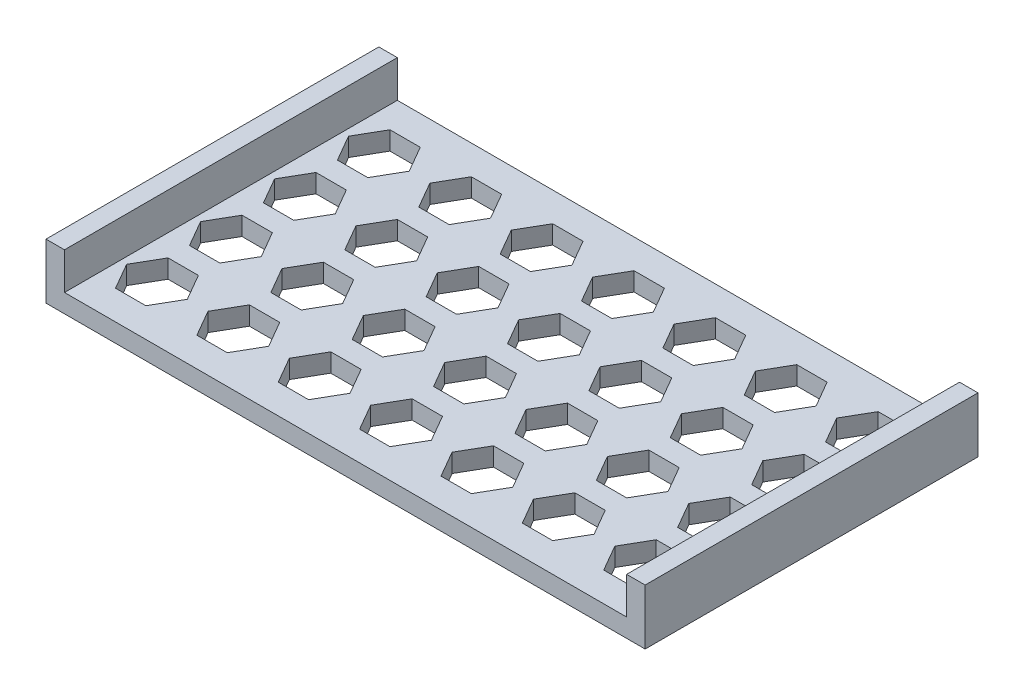
SolidWorks part; units mm, degrees
ref_plane "Front Plane" through (0, 0, 0) normal (0, 0, 1) x (1, 0, 0)
ref_plane "Top Plane" through (0, 0, 0) normal (0, 1, 0) x (1, 0, 0)
ref_plane "Right Plane" through (0, 0, 0) normal (1, 0, 0) x (0, 0, -1)
sketch "Sketch1" plane through (0, 0, 0) normal (0, 1, 0) x (1, 0, 0)
  line L157 (-224.6542, 158.1655) -> (-62.6542, 158.1655)
  line L158 (-224.6542, 158.1655) -> (-224.6542, 68.1655)
  line L159 (-224.6542, 68.1655) -> (-62.6542, 68.1655)
  line L160 (-62.6542, 158.1655) -> (-62.6542, 68.1655)
  dimension "D1" = 90
  dimension "D2" = 162
extrude "Boss-Extrude1" add sketch "Sketch1" along normal blind 5
sketch "Sketch2" plane through (0, 5, 0) normal (0, 1, 0) x (1, 0, 0)
  line L0 (-224.6542, 68.1655) -> (-62.6542, 68.1655) construction
  line L1 (-224.6542, 158.1655) -> (-219.6542, 158.1655)
  line L2 (-224.6542, 158.1655) -> (-224.6542, 68.1655)
  line L3 (-224.6542, 68.1655) -> (-219.6542, 68.1655)
  line L4 (-219.6542, 158.1655) -> (-219.6542, 68.1655)
  line L6 (-62.6542, 158.1655) -> (-67.6542, 158.1655)
  line L7 (-62.6542, 158.1655) -> (-62.6542, 68.1655)
  line L8 (-62.6542, 68.1655) -> (-67.6542, 68.1655)
  line L9 (-67.6542, 158.1655) -> (-67.6542, 68.1655)
  dimension "D1" = 5
  dimension "D2" = 5
extrude "Boss-Extrude2" add sketch "Sketch2" along normal blind 10
sketch "Sketch3" plane through (0, 0, 0) normal (0, -1, 0) x (-1, 0, 0)
  line L5 (62.6542, 158.1655) -> (224.6542, 158.1655) construction
  line L36 (224.6542, 68.1655) -> (209.6542, 68.1655)
  line L37 (224.6542, 68.1655) -> (224.6542, 158.1655)
  line L38 (224.6542, 158.1655) -> (209.6542, 158.1655)
  line L39 (209.6542, 68.1655) -> (209.6542, 158.1655)
  line L40 (62.6542, 68.1655) -> (62.6542, 158.1655) construction
  line L41 (224.6542, 68.1655) -> (62.6542, 68.1655)
  line L42 (224.6542, 68.1655) -> (224.6542, 83.1655)
  line L43 (224.6542, 83.1655) -> (195.6542, 83.1655)
  line L44 (62.6542, 68.1655) -> (62.6542, 83.1655)
  line L87 (195.8542, 83.1655) -> (191.7542, 90.2669)
  line L88 (217.8542, 83.1655) -> (213.7542, 90.2669)
  line L89 (213.7542, 90.2669) -> (205.5542, 90.2669)
  line L90 (205.5542, 90.2669) -> (201.4542, 83.1655)
  line L91 (201.4542, 83.1655) -> (205.5542, 76.0641)
  line L92 (205.5542, 76.0641) -> (213.7542, 76.0641)
  line L93 (213.7542, 76.0641) -> (217.8542, 83.1655)
  line L94 (191.7542, 90.2669) -> (183.5542, 90.2669)
  line L95 (183.5542, 90.2669) -> (179.4542, 83.1655)
  line L96 (179.4542, 83.1655) -> (183.5542, 76.0641)
  line L97 (183.5542, 76.0641) -> (191.7542, 76.0641)
  line L98 (191.7542, 76.0641) -> (195.8542, 83.1655)
  line L99 (173.8542, 83.1655) -> (169.7542, 90.2669)
  line L100 (169.7542, 90.2669) -> (161.5542, 90.2669)
  line L101 (161.5542, 90.2669) -> (157.4542, 83.1655)
  line L102 (157.4542, 83.1655) -> (161.5542, 76.0641)
  line L103 (161.5542, 76.0641) -> (169.7542, 76.0641)
  line L104 (169.7542, 76.0641) -> (173.8542, 83.1655)
  line L105 (151.8542, 83.1655) -> (147.7542, 90.2669)
  line L106 (147.7542, 90.2669) -> (139.5542, 90.2669)
  line L107 (139.5542, 90.2669) -> (135.4542, 83.1655)
  line L108 (135.4542, 83.1655) -> (139.5542, 76.0641)
  line L109 (139.5542, 76.0641) -> (147.7542, 76.0641)
  line L110 (147.7542, 76.0641) -> (151.8542, 83.1655)
  line L111 (129.8542, 83.1655) -> (125.7542, 90.2669)
  line L112 (125.7542, 90.2669) -> (117.5542, 90.2669)
  line L113 (117.5542, 90.2669) -> (113.4542, 83.1655)
  line L114 (113.4542, 83.1655) -> (117.5542, 76.0641)
  line L115 (117.5542, 76.0641) -> (125.7542, 76.0641)
  line L116 (125.7542, 76.0641) -> (129.8542, 83.1655)
  line L117 (107.8542, 83.1655) -> (103.7542, 90.2669)
  line L118 (103.7542, 90.2669) -> (95.5542, 90.2669)
  line L119 (95.5542, 90.2669) -> (91.4542, 83.1655)
  line L120 (91.4542, 83.1655) -> (95.5542, 76.0641)
  line L121 (95.5542, 76.0641) -> (103.7542, 76.0641)
  line L122 (103.7542, 76.0641) -> (107.8542, 83.1655)
  line L123 (85.8542, 83.1655) -> (81.7542, 90.2669)
  line L124 (81.7542, 90.2669) -> (73.5542, 90.2669)
  line L125 (73.5542, 90.2669) -> (69.4542, 83.1655)
  line L126 (69.4542, 83.1655) -> (73.5542, 76.0641)
  line L127 (73.5542, 76.0641) -> (81.7542, 76.0641)
  line L128 (81.7542, 76.0641) -> (85.8542, 83.1655)
  circle A0 centre (209.6542, 83.1655) radius 7.1014 construction
  dimension "D1" = 15
  dimension "D2" = 15
  dimension "D3" = 8.2
  dimension "D4" = 7
extrude "Cut-Extrude1" cut sketch "Sketch3" against normal blind 10
pattern_linear "LPattern2" count 7 spacing 22 along (1, 0, 0) of "Cut-Extrude1"
pattern_linear "LPattern3" count 4 spacing 20 along (0, 0, -1) of "LPattern2", "Cut-Extrude1"
